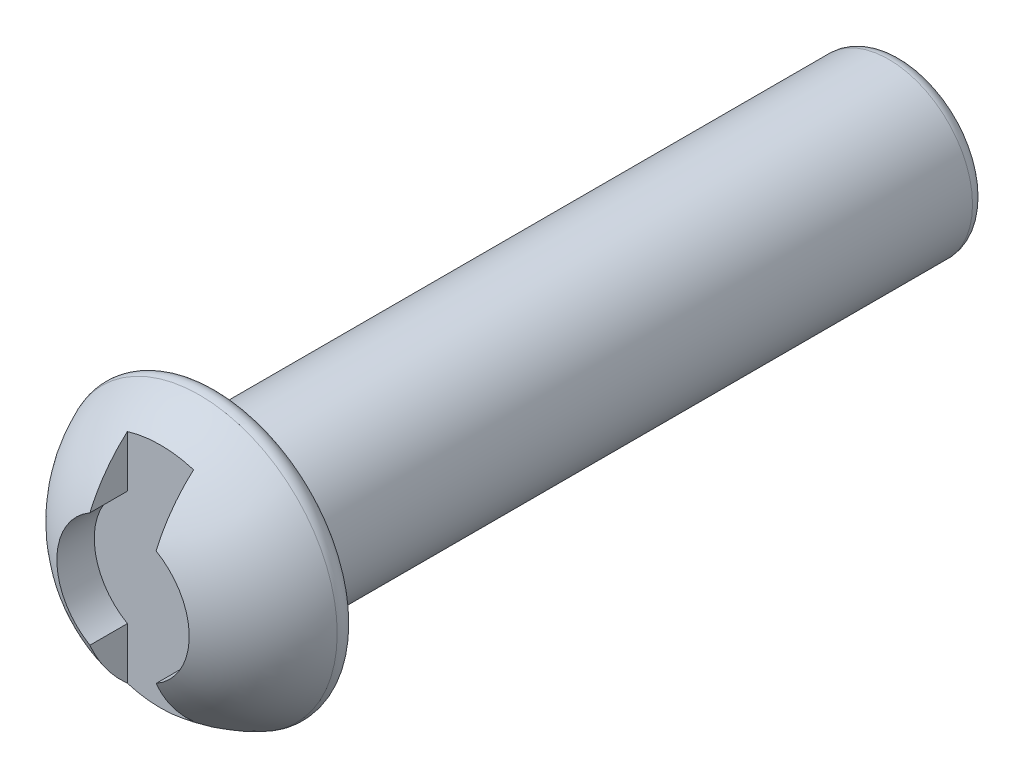
SolidWorks part; units mm, degrees
ref_plane "Front Plane" through (0, 0, 0) normal (0, 0, 1) x (1, 0, 0)
ref_plane "Top Plane" through (0, 0, 0) normal (0, 1, 0) x (1, 0, 0)
ref_plane "Right Plane" through (0, 0, 0) normal (1, 0, 0) x (0, 0, -1)
sketch "Sketch4" plane through (0, 0, 0) normal (1, 0, 0) x (0, 0, -1)
  line L0 (0, 0) -> (9, 0)
  line L1 (9, 0) -> (9, 0.95)
  line L2 (9, 0.95) -> (1.25, 0.95)
  line L3 (1.25, 1.63) -> (1.25, 0.95)
  arc A0 (1.25, 1.63) -> (0, 0) centre (1.6878, 0) ccw
  dimension "D1" = 9
  dimension "D2" = 0.95
  dimension "D3" = 1.63
  dimension "D4" = 1.25
revolve "Revolve2" add sketch "Sketch4" angle 360 about L0
sketch "Sketch5" plane through (0, 0, 0) normal (0, 0, 1) x (1, 0, 0)
  line L0 (-0.375, -0.6495) -> (-0.375, -1.871)
  line L1 (0.375, 1.871) -> (-0.375, 1.871)
  line L2 (0.375, 1.871) -> (0.375, 0.6495)
  line L3 (0.375, -1.871) -> (-0.375, -1.871)
  line L4 (-0.375, 1.871) -> (-0.375, 0.6495)
  line L9 (0.375, -0.6495) -> (0.375, -1.871)
  arc A0 (-0.375, 0.6495) -> (-0.375, -0.6495) centre (0, 0) ccw
  arc A1 (0.375, -0.6495) -> (0.375, 0.6495) centre (0, 0) ccw
  point P0 (0, 0)
  dimension "D2" = 1.5
  dimension "D1" = 0.75
extrude "Cut-Extrude1" cut sketch "Sketch5" against normal blind 0.6
fillet "Fillet1" radius 0.15 2 edges at (1.63, 0, -1.25) (0.95, 0, -9)
